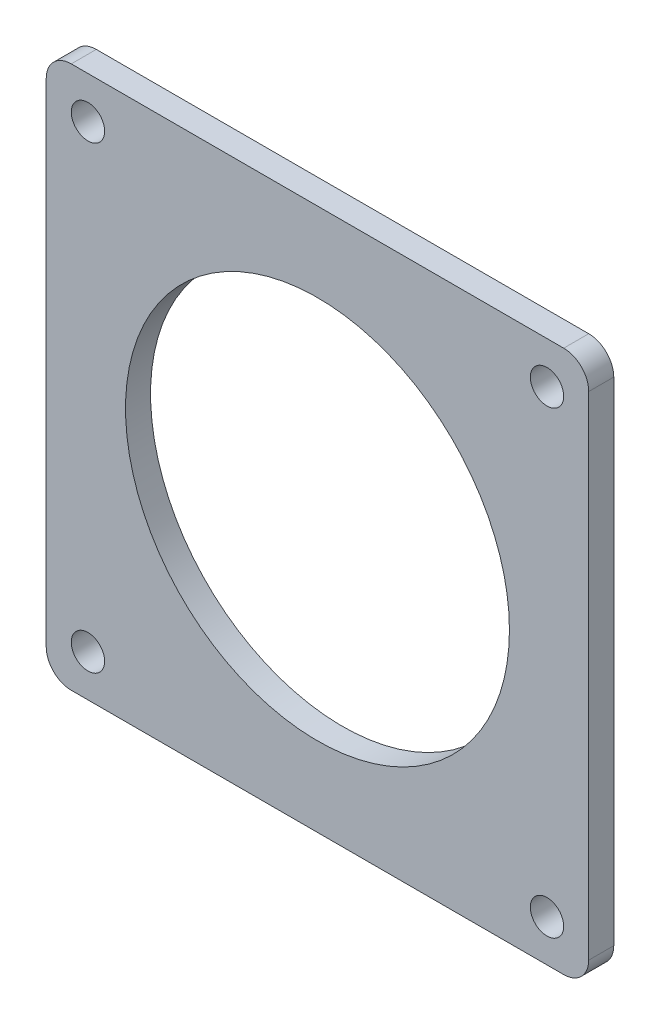
SolidWorks part; units mm, degrees
ref_plane "前视基准面" through (0, 0, 0) normal (0, 0, 1) x (1, 0, 0)
ref_plane "上视基准面" through (0, 0, 0) normal (0, 1, 0) x (1, 0, 0)
ref_plane "右视基准面" through (0, 0, 0) normal (1, 0, 0) x (0, 0, -1)
other "Configuration Table"
sketch "草图1" plane through (0, 0, 0) normal (0, 0, 1) x (1, 0, 0)
  line L1 (-32.5, 32.5) -> (32.5, 32.5)
  line L2 (-32.5, 32.5) -> (-32.5, -32.5)
  line L3 (-32.5, -32.5) -> (32.5, -32.5)
  line L4 (32.5, 32.5) -> (32.5, -32.5)
  line L5 (-32.5, 32.5) -> (32.5, -32.5) construction
  line L6 (-32.5, -32.5) -> (32.5, 32.5) construction
  line L7 (-27.5, 27.5) -> (27.5, 27.5) construction
  line L8 (-27.5, 27.5) -> (-27.5, -27.5) construction
  line L9 (-27.5, -27.5) -> (27.5, -27.5) construction
  line L10 (27.5, 27.5) -> (27.5, -27.5) construction
  line L11 (-27.5, 27.5) -> (27.5, -27.5) construction
  line L12 (-27.5, -27.5) -> (27.5, 27.5) construction
  circle A0 centre (-27.5, 27.5) radius 2
  circle A1 centre (27.5, 27.5) radius 2
  circle A2 centre (27.5, -27.5) radius 2
  circle A3 centre (-27.5, -27.5) radius 2
  circle A4 centre (0, 0) radius 23
  point P0 (0, 0)
  point P5 (0, 0)
  dimension "D3" = 4
  dimension "D4" = 4
  dimension "D5" = 4
  dimension "D6" = 4
  dimension "D7" = 46
  dimension "D1" = 65
  dimension "D2" = 55
extrude "凸台-拉伸1" add sketch "草图1" along normal blind 3
fillet "圆角1" radius 3 4 edges at (-32.5, 32.5, 1.5) (-32.5, -32.5, 1.5) (32.5, -32.5, 1.5) (32.5, 32.5, 1.5)
